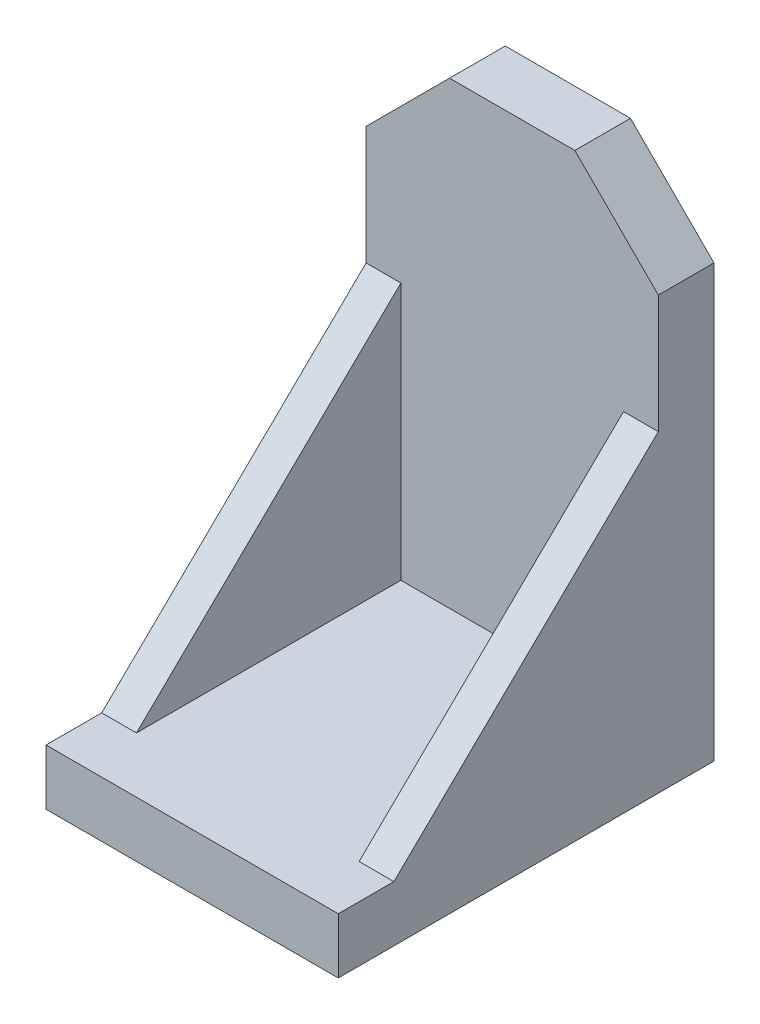
SolidWorks part; units mm, degrees
ref_plane "Front Plane" through (0, 0, 0) normal (0, 0, 1) x (1, 0, 0)
ref_plane "Top Plane" through (0, 0, 0) normal (0, 1, 0) x (1, 0, 0)
ref_plane "Right Plane" through (0, 0, 0) normal (1, 0, 0) x (0, 0, -1)
sketch "Sketch1" plane through (0, 0, 0) normal (0, 0, 1) x (1, 0, 0)
  line L0 (0, 0) -> (0, 62)
  line L1 (0, 62) -> (12, 74)
  line L2 (12, 74) -> (30, 74)
  line L3 (30, 74) -> (42, 62)
  line L4 (42, 62) -> (42, 0)
  line L5 (42, 0) -> (0, 0)
  line L6 (21, 0) -> (21, 88.9149) construction
  point P9 (21, 74)
  dimension "D1" = 42
  dimension "D2" = 62
  dimension "D3" = 62
  dimension "D4" = 18
extrude "Boss-Extrude1" add sketch "Sketch1" along normal blind 8
sketch "Sketch2" plane through (0, 0, 8) normal (0, 0, 1) x (1, 0, 0)
  line L0 (0, 0) -> (42, 0)
  line L1 (42, 0) -> (42, 8)
  line L2 (42, 0) -> (42, 62) construction
  line L3 (42, 8) -> (0, 8)
  line L4 (0, 62) -> (0, 0) construction
  line L5 (0, 8) -> (0, 0)
  point P10 (42, 4)
  dimension "D1" = 8
extrude "Boss-Extrude2" add sketch "Sketch2" along normal blind 46
sketch "Sketch3" plane through (42, 0, 0) normal (1, 0, 0) x (0, 0, -1)
  line L0 (-8, 8) -> (-8, 45)
  line L1 (-8, 8) -> (-8, 62) construction
  line L2 (-8, 45) -> (-46, 8)
  line L3 (-54, 8) -> (-8, 8) construction
  line L4 (-46, 8) -> (-8, 8)
  line L5 (-54, 0) -> (-54, 8) construction
  line L6 (-8, 62) -> (0, 62) construction
  dimension "D1" = 8
  dimension "D2" = 17
extrude "Boss-Extrude3" add sketch "Sketch3" against normal blind 5
ref_plane "Plane1" through (21, 0, 0) normal (1, 0, 0) x (0, 0, -1)
mirror "Mirror1" about plane through (21, 0, 0) normal (1, 0, 0) of bodies 103
sketch "Sketch4" plane through (0, 0, 8) normal (0, 0, 1) x (1, 0, 0)
  line L0 (30, 74) -> (12, 74) construction
  line L1 (21, 74) -> (21, 30.859) construction
  circle A0 centre (21, 54) radius 7
  circle A1 centre (21, 54) radius 7
  dimension "D1" = 14
  dimension "D2" = 20
